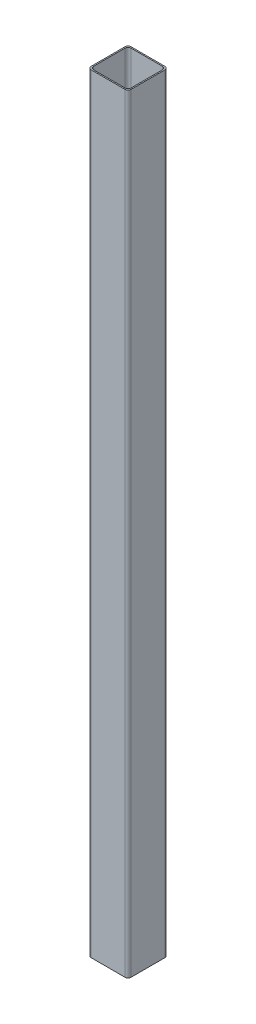
SolidWorks part; units mm, degrees
ref_plane "Plano frontal" through (0, 0, 0) normal (0, 0, 1) x (1, 0, 0)
ref_plane "Plano superior" through (0, 0, 0) normal (0, 1, 0) x (1, 0, 0)
ref_plane "Plano direito" through (0, 0, 0) normal (1, 0, 0) x (0, 0, -1)
sketch "Esboço1" plane through (0, 0, 0) normal (0, 1, 0) x (1, 0, 0)
  line L0 (-18.8, -18.8) -> (-18.8, 18.8)
  line L1 (20, -20) -> (-20, -20)
  line L2 (20, -20) -> (20, 20)
  line L3 (20, 20) -> (-20, 20)
  line L4 (-20, -20) -> (-20, 20)
  line L5 (20, -20) -> (-20, 20) construction
  line L6 (20, 20) -> (-20, -20) construction
  line L7 (18.8, 18.8) -> (-18.8, 18.8)
  line L8 (18.8, -18.8) -> (18.8, 18.8)
  line L9 (18.8, -18.8) -> (-18.8, -18.8)
  point P0 (0, 0)
  dimension "D1" = 40
  dimension "D2" = 40
  dimension "D3" = 1.2
extrude "Ressalto-extrusão1" add sketch "Esboço1" along normal mid plane 770
fillet "Filete1" radius 3 8 edges at (-20, 0, -20) (20, 0, -20) (18.8, 0, -18.8) (18.8, 0, 18.8) (-18.8, 0, 18.8) (-18.8, 0, -18.8) (-20, 0, 20) (20, 0, 20)
